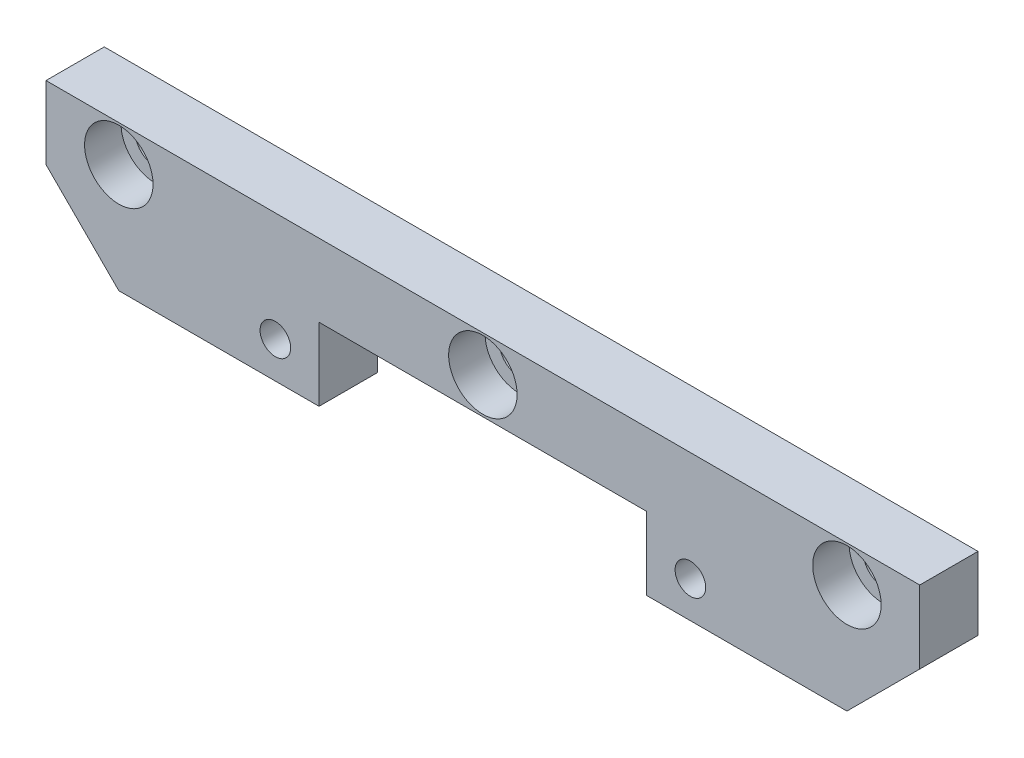
SolidWorks part; units mm, degrees
material "45#"
ref_plane "前视" through (0, 0, 0) normal (0, 0, 1) x (1, 0, 0)
ref_plane "上视" through (0, 0, 0) normal (0, 1, 0) x (1, 0, 0)
ref_plane "右视" through (0, 0, 0) normal (1, 0, 0) x (0, 0, -1)
sketch "草图1" plane through (0, 0, 0) normal (0, 0, 1) x (1, 0, 0)
  line L1 (-60, -10) -> (60, -10)
  line L2 (-60, -10) -> (-60, 10)
  line L3 (-60, 10) -> (60, 10)
  line L4 (60, -10) -> (60, 10)
  line L5 (-60, -10) -> (60, 10) construction
  line L6 (-60, 10) -> (60, -10) construction
  point P0 (0, 0)
  dimension "D1" = 120
  dimension "D2" = 20
extrude "凸台-拉伸1" add sketch "草图1" along normal mid plane 8
hole_wizard "打孔尺寸根据内六角圆柱头螺钉的类型1" positions "草图3" profile "草图2" counterbore size "M5" standard "Gb" end condition through all
sketch "草图3" plane through (-5.3323, -2.4196, 4) normal (0, 0, -1) x (1, 0, 0)
  line L2 (5.3323, 2.5804) -> (5.3323, 7.5804) construction
  line L4 (-54.6677, 7.5804) -> (65.3323, 7.5804) construction
  line L6 (65.3323, -12.4196) -> (-54.6677, -12.4196) construction
  point P0 (-44.6677, -7.4196)
  point P13 (55.3323, -7.4196)
  point P30 (5.3323, -7.4196)
  dimension "D1" = 100
  dimension "D2" = 5
sketch "草图2" plane through (-50, 5, 4) normal (1, 0, 0) x (0, -1, 0)
  line L0 (0, 0) -> (0, 8)
  line L1 (0, 8) -> (2.75, 8)
  line L3 (2.75, 8) -> (2.75, 5)
  line L4 (2.75, 5) -> (4.7, 5)
  line L5 (4.7, 5) -> (4.7, 0)
  line L7 (4.7, 0) -> (0, 0)
  line L11 (0, -6.35) -> (0, 107.95) construction
  dimension "通孔孔直径" = 5.5
  dimension "通孔孔深度" = 8
  dimension "柱形沉头孔直径" = 9.4
  dimension "柱形沉头孔深度" = 5
hole_wizard "M5 螺纹孔2" positions "草图5" profile "草图4" tap size "M5" standard "Gb" end condition through all
sketch "草图5" plane through (0, 0, 4) normal (0, 0, 1) x (1, 0, 0)
  line L0 (0, 10) -> (0, -6.9542) construction
  line L1 (60, 10) -> (-60, 10) construction
  circle A0 centre (50, 5) radius 4.7 construction
  point P0 (-28.5, -5)
  point P10 (28.5, -5)
  dimension "D1" = 57
  dimension "D2" = 10
sketch "草图4" plane through (-28.5, -5, 4) normal (1, 0, 0) x (0, -1, 0)
  line L0 (0, 0) -> (0, 8)
  line L1 (0, 8) -> (2.1, 8)
  line L2 (2.1, 8) -> (2.1, 0)
  line L5 (2.1, 0) -> (0, 0)
  line L11 (0, -6.35) -> (0, 107.95) construction
  dimension "通孔螺纹孔钻头直径" = 4.2
  dimension "通孔螺纹孔钻头深度" = 8
cosmetic thread "孔螺蚊线3" parameters "D2"=5
cosmetic thread "孔螺蚊线4" parameters "D2"=5
sketch "草图6" plane through (0, 0, 4) normal (0, 0, 1) x (1, 0, 0)
  line L0 (0, -10) -> (0, 10) construction
  line L1 (-60, -10) -> (60, -10) construction
  line L2 (60, 10) -> (-60, 10) construction
  line L4 (-22.5, 0) -> (22.5, 0)
  line L5 (-22.5, 0) -> (-22.5, -10)
  line L6 (-22.5, -10) -> (22.5, -10)
  line L7 (22.5, 0) -> (22.5, -10)
  line L8 (-22.5, 0) -> (22.5, -10) construction
  line L9 (-22.5, -10) -> (22.5, 0) construction
  point P6 (0, -5)
  dimension "D1" = 45
  dimension "D2" = 10
extrude "切除-拉伸1" cut sketch "草图6" against normal through all
chamfer "倒角1" distance 10 angle 45 2 edges at (60, -10, 0) (-60, -10, 0)
